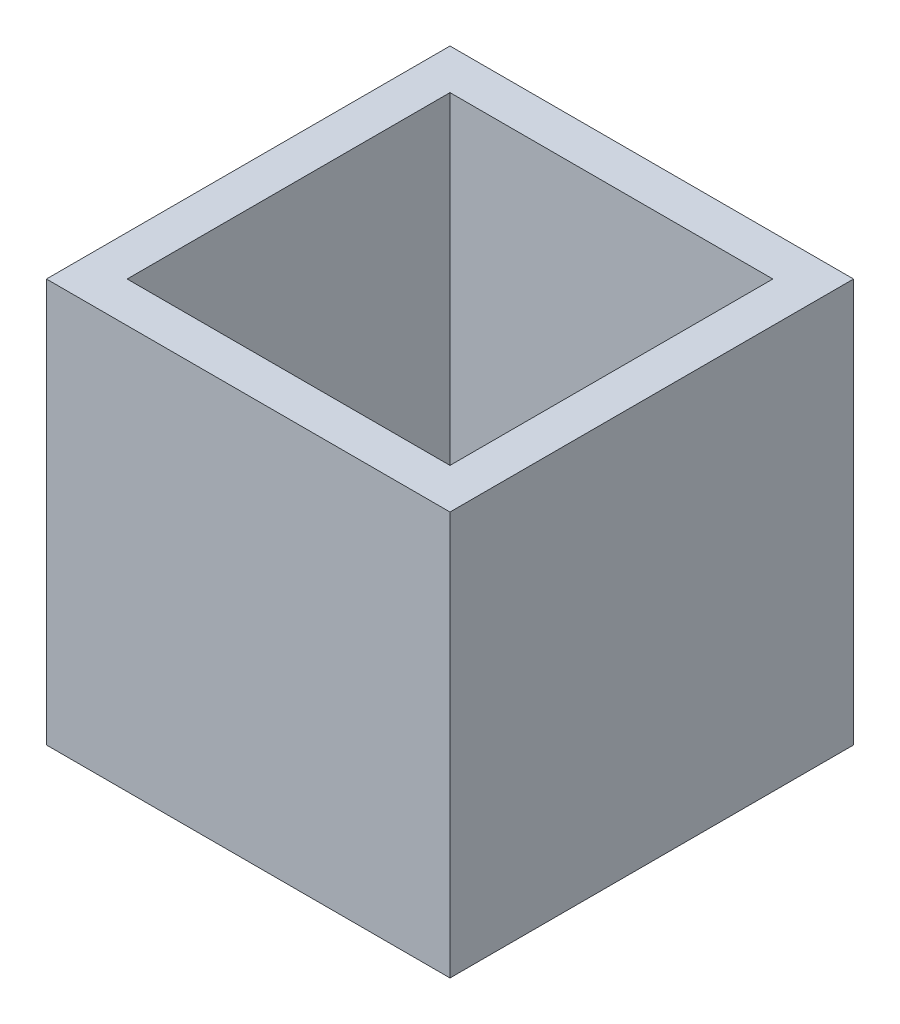
SolidWorks part; units mm, degrees
ref_plane "Front Plane" through (0, 0, 0) normal (0, 0, 1) x (1, 0, 0)
ref_plane "Top Plane" through (0, 0, 0) normal (0, 1, 0) x (1, 0, 0)
ref_plane "Right Plane" through (0, 0, 0) normal (1, 0, 0) x (0, 0, -1)
sketch "Sketch1" plane through (0, 0, 0) normal (0, 1, 0) x (1, 0, 0)
  line L1 (-1.25, -1.25) -> (1.25, -1.25)
  line L2 (-1.25, -1.25) -> (-1.25, 1.25)
  line L3 (-1.25, 1.25) -> (1.25, 1.25)
  line L4 (1.25, -1.25) -> (1.25, 1.25)
  line L5 (-1.25, -1.25) -> (1.25, 1.25) construction
  line L6 (-1.25, 1.25) -> (1.25, -1.25) construction
  line L7 (-1, -1) -> (1, -1)
  line L8 (-1, -1) -> (-1, 1)
  line L9 (-1, 1) -> (1, 1)
  line L10 (1, -1) -> (1, 1)
  line L11 (-1, -1) -> (1, 1) construction
  line L12 (-1, 1) -> (1, -1) construction
  point P0 (0, 0)
  point P6 (0, 0)
  dimension "D1" = 2.5
  dimension "D2" = 2.5
  dimension "D3" = 2
extrude "Boss-Extrude1" add sketch "Sketch1" along normal blind 2.5
scale "Scale1" scale about centroid uniform scaling yes scale factor 6
